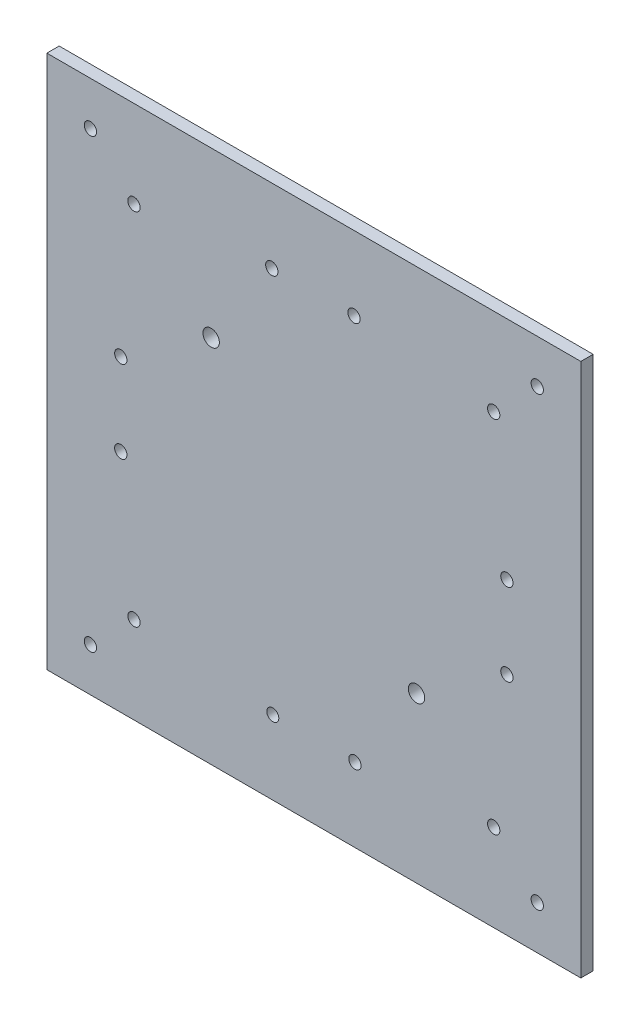
SolidWorks part; units mm, degrees
ref_plane "前视基准面" through (0, 0, 0) normal (0, 0, 1) x (1, 0, 0)
ref_plane "上视基准面" through (0, 0, 0) normal (0, 1, 0) x (1, 0, 0)
ref_plane "右视基准面" through (0, 0, 0) normal (1, 0, 0) x (0, 0, -1)
sketch "草图1" plane through (0, 0, 0) normal (0, 0, 1) x (1, 0, 0)
  line L1 (65, -65) -> (-65, -65)
  line L2 (65, -65) -> (65, 65)
  line L3 (65, 65) -> (-65, 65)
  line L4 (-65, -65) -> (-65, 65)
  line L5 (65, -65) -> (-65, 65) construction
  line L6 (65, 65) -> (-65, -65) construction
  point P0 (0, 0)
  dimension "D1" = 130
  dimension "D2" = 130
extrude "凸台-拉伸1" add sketch "草图1" along normal blind 3
sketch "草图5" plane through (0, 0, 3) normal (0, 0, 1) x (1, 0, 0)
  line L1 (25, -25) -> (-25, -25) construction
  line L2 (25, -25) -> (25, 25) construction
  line L3 (25, 25) -> (-25, 25) construction
  line L4 (-25, -25) -> (-25, 25) construction
  line L5 (25, -25) -> (-25, 25) construction
  line L6 (25, 25) -> (-25, -25) construction
  circle A0 centre (25, -25) radius 2
  circle A1 centre (-25, 25) radius 2
  point P0 (0, 0)
  dimension "D3" = 4
  dimension "D4" = 4
  dimension "D1" = 50
  dimension "D2" = 50
extrude "切除-拉伸4" cut sketch "草图5" against normal blind 3
sketch "草图6" plane through (0, 0, 3) normal (0, 0, 1) x (1, 0, 0)
  circle A0 centre (-54.3934, 54.3934) radius 1.5
  circle A1 centre (-43.7868, 43.7868) radius 1.5
  circle A2 centre (-10.2329, 47) radius 1.5
  circle A3 centre (9.7671, 47) radius 1.5
  circle A4 centre (43.7868, 43.7868) radius 1.5
  circle A5 centre (54.3934, 54.3934) radius 1.5
  circle A6 centre (-47, 10) radius 1.5
  circle A7 centre (-47, -10) radius 1.5
  circle A8 centre (47, -10) radius 1.5
  circle A9 centre (47, 10) radius 1.5
  circle A10 centre (-54.3934, -54.3934) radius 1.5
  circle A11 centre (-43.7868, -43.7868) radius 1.5
  circle A12 centre (-10, -47) radius 1.465
  circle A13 centre (10, -47) radius 1.5
  circle A14 centre (43.7868, -43.7868) radius 1.5
  circle A15 centre (54.3934, -54.3934) radius 1.5
extrude "切除-拉伸5" cut sketch "草图6" against normal blind 10
